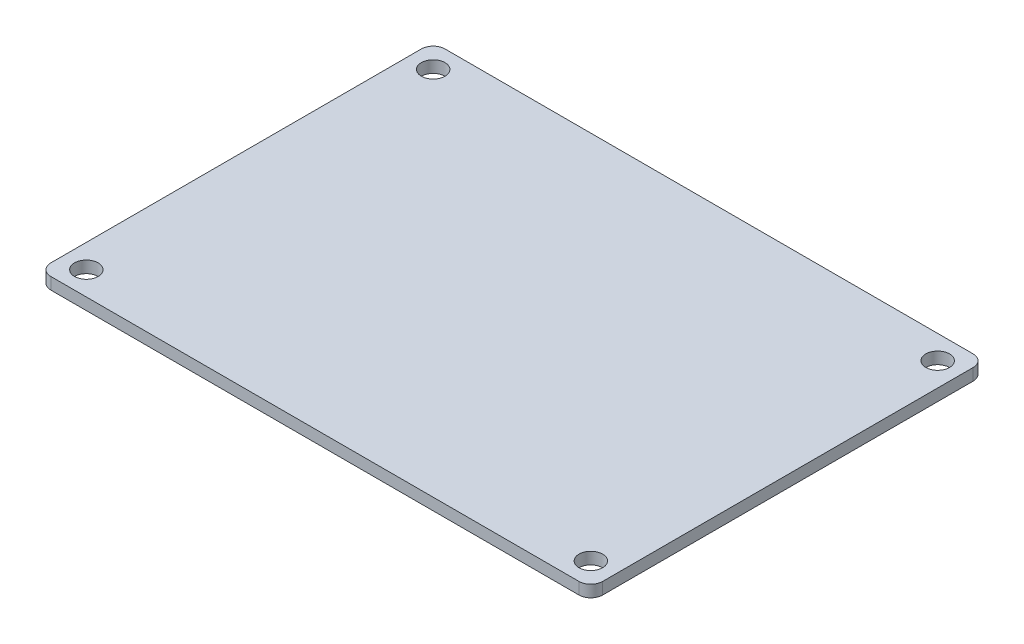
SolidWorks part; units mm, degrees
ref_plane "Front Plane" through (0, 0, 0) normal (0, 0, 1) x (1, 0, 0)
ref_plane "Top Plane" through (0, 0, 0) normal (0, 1, 0) x (1, 0, 0)
ref_plane "Right Plane" through (0, 0, 0) normal (1, 0, 0) x (0, 0, -1)
sketch "Sketch1" plane through (0, 0, 0) normal (0, 1, 0) x (1, 0, 0)
  line L1 (-35, -25) -> (35, -25)
  line L2 (-35, -25) -> (-35, 25)
  line L3 (-35, 25) -> (35, 25)
  line L4 (35, -25) -> (35, 25)
  line L5 (-35, -25) -> (35, 25) construction
  line L6 (-35, 25) -> (35, -25) construction
  point P0 (0, 0)
  dimension "D1" = 70
  dimension "D2" = 50
extrude "Boss-Extrude1" add sketch "Sketch1" along normal blind 1.5
sketch "Sketch2" plane through (0, 1.5, 0) normal (0, 1, 0) x (1, 0, 0)
  line L0 (-35, -25) -> (35, -25) construction
  line L1 (-35, 25) -> (-35, -25) construction
  circle A0 centre (-32, -22) radius 1.5
  circle A1 centre (32, -22) radius 1.5
  circle A2 centre (32, 22) radius 1.5
  circle A3 centre (-32, 22) radius 1.5
  dimension "D1" = 3
  dimension "D2" = 3
  dimension "D3" = 3
  dimension "D4" = 2
  dimension "D5" = 2
extrude "Cut-Extrude1" cut sketch "Sketch2" against normal blind 10
fillet "Fillet1" radius 1.5 4 edges at (-35, 0.75, -25) (35, 0.75, -25) (35, 0.75, 25) (-35, 0.75, 25)
